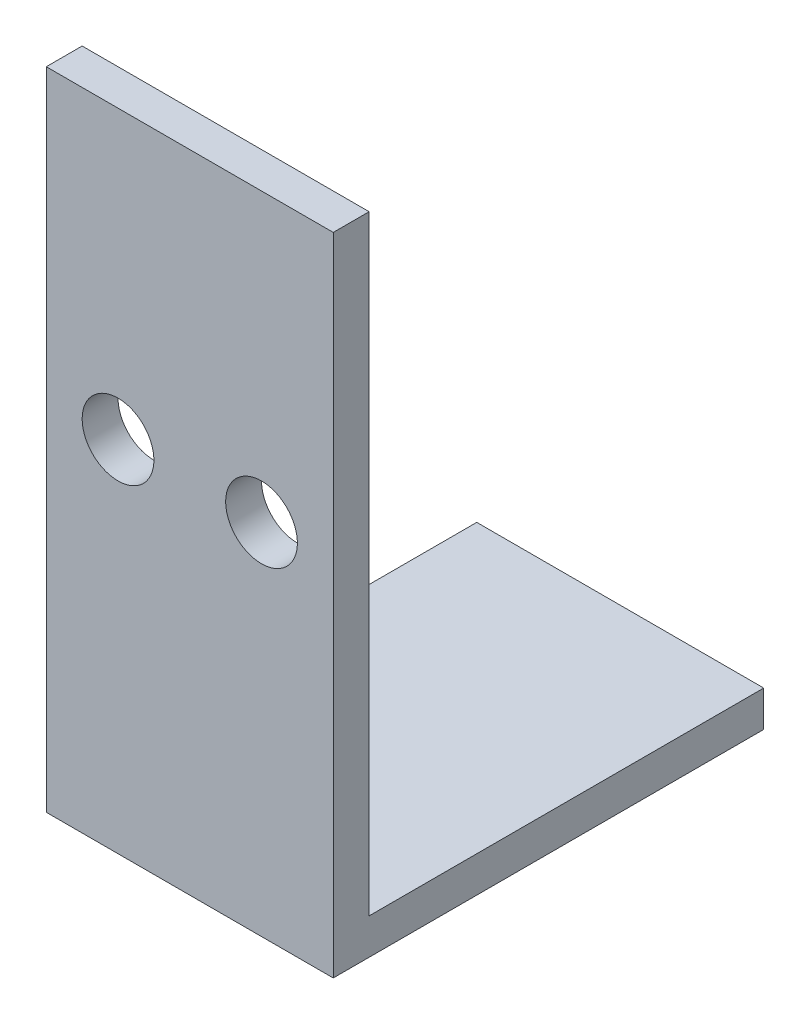
SolidWorks part; units mm, degrees
material "6061-T6 (SS)"
ref_plane "Front Plane" through (0, 0, 0) normal (0, 0, 1) x (1, 0, 0)
ref_plane "Top Plane" through (0, 0, 0) normal (0, 1, 0) x (1, 0, 0)
ref_plane "Right Plane" through (0, 0, 0) normal (1, 0, 0) x (0, 0, -1)
sketch "Sketch1" plane through (0, 0, 0) normal (1, 0, 0) x (0, 0, -1)
  line L0 (38.1, 3.175) -> (0, 3.175)
  line L1 (0, 0) -> (3.175, 0)
  line L2 (0, 0) -> (0, 57.15)
  line L3 (0, 57.15) -> (3.175, 57.15)
  line L4 (3.175, 0) -> (3.175, 57.15)
  line L5 (0, 0) -> (38.1, 0)
  line L6 (0, 0) -> (0, 3.175)
  line L8 (38.1, 0) -> (38.1, 3.175)
  dimension "D1" = 57.15
  dimension "D2" = 3.175
  dimension "D3" = 38.1
extrude "Boss-Extrude1" add sketch "Sketch1" along normal blind 25.4
sketch "Sketch2" plane through (0, 0, -3.175) normal (0, 0, -1) x (-1, 0, 0)
  line L0 (-25.4, 3.175) -> (-25.4, 57.15) construction
  line L1 (0, 3.175) -> (0, 57.15) construction
  line L3 (-25.4, 57.15) -> (0, 57.15) construction
  line L4 (-25.4, 57.15) -> (0, 57.15) construction
  circle A0 centre (-19.05, 31.75) radius 3.175
  circle A1 centre (-6.35, 31.75) radius 3.175
  dimension "D1" = 6.35
  dimension "D2" = 6.35
  dimension "D3" = 6.35
  dimension "D4" = 6.35
  dimension "D5" = 25.4
  dimension "D6" = 25.4
extrude "Cut-Extrude1" cut sketch "Sketch2" against normal through all
